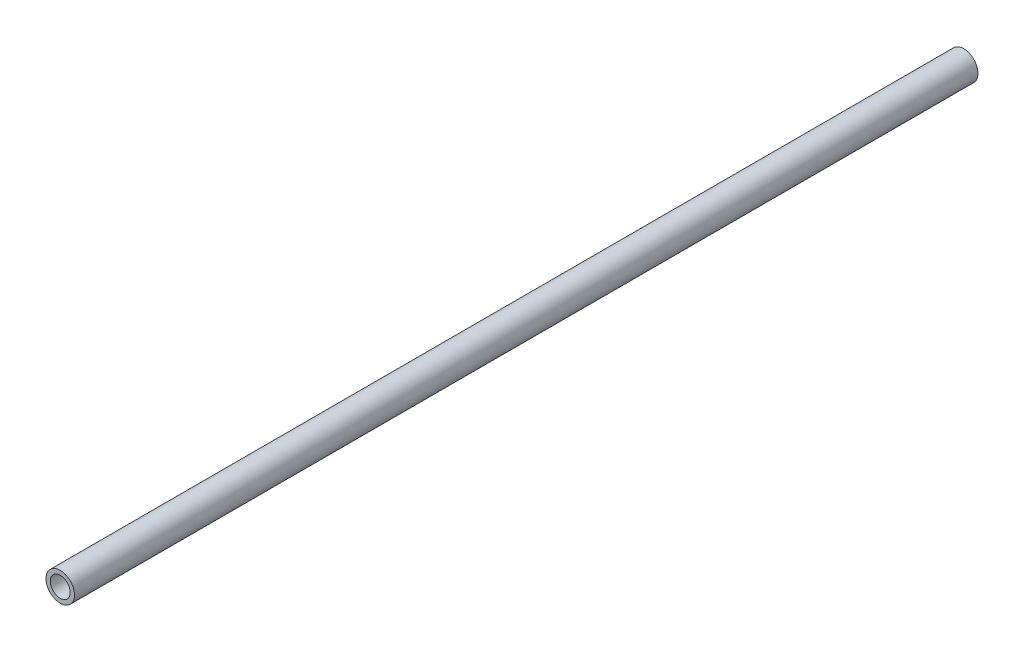
SolidWorks part; units mm, degrees
material "Maple"
ref_plane "Front Plane" through (0, 0, 0) normal (0, 0, 1) x (1, 0, 0)
ref_plane "Top Plane" through (0, 0, 0) normal (0, 1, 0) x (1, 0, 0)
ref_plane "Right Plane" through (0, 0, 0) normal (1, 0, 0) x (0, 0, -1)
sketch "Sketch1" plane through (0, 0, 0) normal (0, 0, 1) x (1, 0, 0)
  circle A0 centre (0, 0) radius 3.81
  dimension "D1" = 7.62
extrude "Boss-Extrude1" add sketch "Sketch1" against normal blind 241.3
sketch "Sketch2" plane through (0, 0, 0) normal (0, 0, 1) x (1, 0, 0)
  circle A0 centre (0, 0) radius 2.667
  dimension "D1" = 5.334
extrude "Cut-Extrude1" cut sketch "Sketch2" against normal through all
